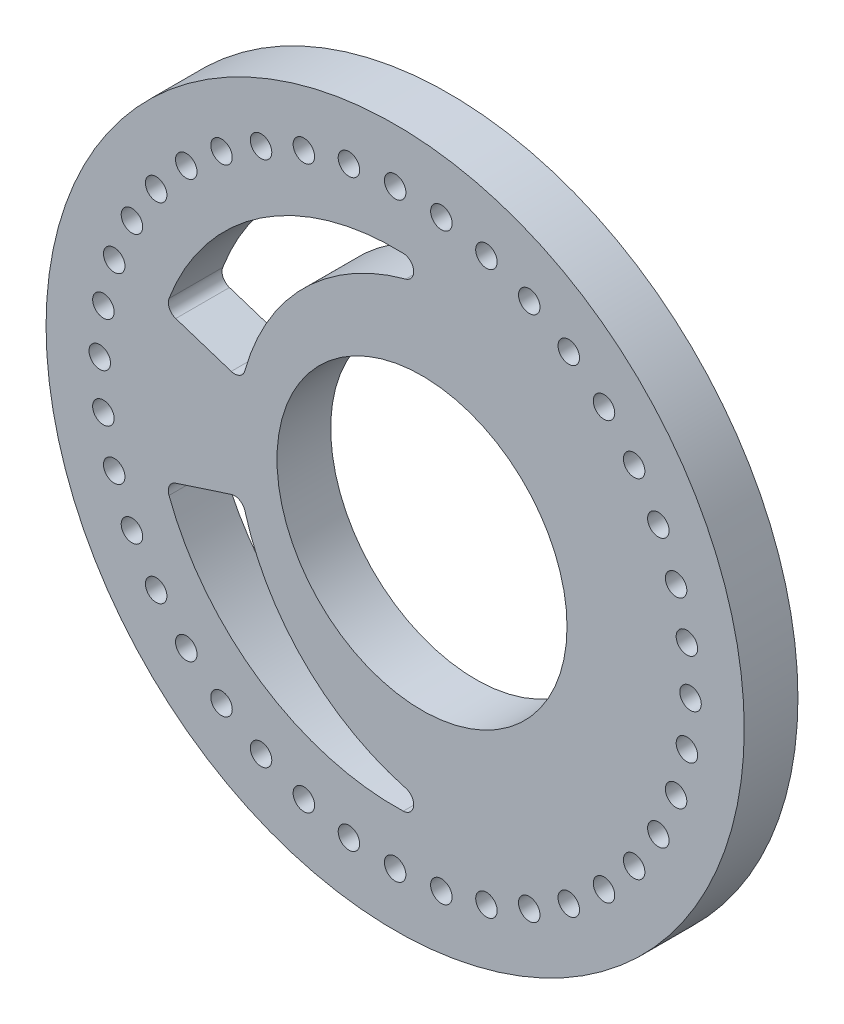
SolidWorks part; units mm, degrees
ref_plane "前视基准面" through (0, 0, 0) normal (0, 0, 1) x (1, 0, 0)
ref_plane "上视基准面" through (0, 0, 0) normal (0, 1, 0) x (1, 0, 0)
ref_plane "右视基准面" through (0, 0, 0) normal (1, 0, 0) x (0, 0, -1)
other "Configuration Table"
sketch "草图5" plane through (0, 0, 0) normal (0, 0, 1) x (1, 0, 0)
  line L0 (-76.63, 0) -> (109.198, 0) construction
  line L1 (-52.3081, 16.9959) -> (-50.406, 16.3779)
  line L2 (-42.7975, 13.9058) -> (0, 0) construction
  line L3 (-42.7975, 13.9058) -> (-28.4803, 9.2538)
  line L4 (-42.7975, -13.9058) -> (-28.4803, -9.2538)
  circle A0 centre (0, 0) radius 65
  circle A1 centre (0, 0) radius 55 construction
  circle A2 centre (55, 0) radius 2
  circle A3 centre (54.3229, -8.6039) radius 2
  circle A4 centre (52.3081, -16.9959) radius 2
  circle A5 centre (49.0054, -24.9695) radius 2
  circle A6 centre (44.4959, -32.3282) radius 2
  circle A7 centre (38.8909, -38.8909) radius 2
  circle A8 centre (32.3282, -44.4959) radius 2
  circle A9 centre (24.9695, -49.0054) radius 2
  circle A10 centre (16.9959, -52.3081) radius 2
  circle A11 centre (8.6039, -54.3229) radius 2
  circle A12 centre (0, -55) radius 2
  circle A13 centre (-8.6039, -54.3229) radius 2
  circle A14 centre (-16.9959, -52.3081) radius 2
  circle A15 centre (-24.9695, -49.0054) radius 2
  circle A16 centre (-32.3282, -44.4959) radius 2
  circle A17 centre (-38.8909, -38.8909) radius 2
  circle A18 centre (-44.4959, -32.3282) radius 2
  circle A19 centre (-49.0054, -24.9695) radius 2
  circle A20 centre (-52.3081, -16.9959) radius 2
  circle A21 centre (-54.3229, -8.6039) radius 2
  circle A22 centre (-55, 0) radius 2
  circle A23 centre (-54.3229, 8.6039) radius 2
  circle A24 centre (-52.3081, 16.9959) radius 2
  circle A25 centre (-49.0054, 24.9695) radius 2
  circle A26 centre (-44.4959, 32.3282) radius 2
  circle A27 centre (-38.8909, 38.8909) radius 2
  circle A28 centre (-32.3282, 44.4959) radius 2
  circle A29 centre (-24.9695, 49.0054) radius 2
  circle A30 centre (-16.9959, 52.3081) radius 2
  circle A31 centre (-8.6039, 54.3229) radius 2
  circle A32 centre (0, 55) radius 2
  circle A33 centre (8.6039, 54.3229) radius 2
  circle A34 centre (16.9959, 52.3081) radius 2
  circle A35 centre (24.9695, 49.0054) radius 2
  circle A36 centre (32.3282, 44.4959) radius 2
  circle A37 centre (38.8909, 38.8909) radius 2
  circle A38 centre (44.4959, 32.3282) radius 2
  circle A39 centre (49.0054, 24.9695) radius 2
  circle A40 centre (52.3081, 16.9959) radius 2
  circle A41 centre (54.3229, 8.6039) radius 2
  circle A42 centre (0, 0) radius 5 construction
  arc A44 (14.9135, 42.4569) -> (-42.7975, 13.9058) centre (0, 0) ccw
  arc A45 (14.9135, 42.4569) -> (-28.4803, 9.2538) centre (13, 0) ccw
  arc A46 (14.9135, -42.4569) -> (-42.7975, -13.9058) centre (0, 0) cw
  arc A47 (14.9135, -42.4569) -> (-28.4803, -9.2538) centre (13, 0) cw
  circle A48 centre (5, 0) radius 27
  point P86 (0, 0)
  dimension "D1" = 130
  dimension "D2" = 110
  dimension "D3" = 4
  dimension "D5" = 10
  dimension "D6" = 54
  dimension "D7" = 90
  dimension "D9" = 85
  dimension "D8" = 13
  dimension "D10" = 18
  dimension "D4" = 40
extrude "凸台-拉伸3" add sketch "草图5" along normal blind 10 contours A0 A47 A46 L4 A48 A41 A40 A39 A38 A37 A36 A35 A34 A33 A32 A31 A30 A29 A28 A27 A26 A25 A24 A23 A22 A21 A20
fillet "圆角1" radius 2 6 edges at (14.9135, -42.4569, 5) (-42.7975, -13.9058, 5) (-28.4803, -9.2538, 5) (-42.7975, 13.9058, 5) (-28.4803, 9.2538, 5) (14.9135, 42.4569, 5)
